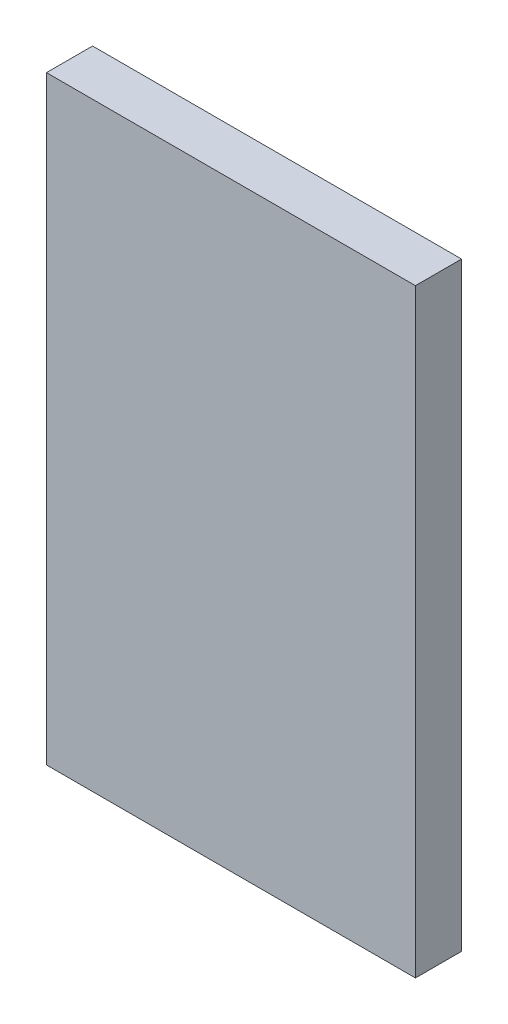
SolidWorks part; units mm, degrees
ref_plane "Front Plane" through (0, 0, 0) normal (0, 0, 1) x (1, 0, 0)
ref_plane "Top Plane" through (0, 0, 0) normal (0, 1, 0) x (1, 0, 0)
ref_plane "Right Plane" through (0, 0, 0) normal (1, 0, 0) x (0, 0, -1)
sketch "Sketch1" plane through (0, 0, 0) normal (0, 0, 1) x (1, 0, 0)
  line L1 (-10, 0) -> (10, 0)
  line L2 (-10, 0) -> (-10, 32.5)
  line L3 (-10, 32.5) -> (10, 32.5)
  line L4 (10, 0) -> (10, 32.5)
  point P4 (0, 0)
  dimension "D1" = 20
  dimension "D2" = 32.5
  dimension "D3" = 0
  dimension "D4" = 10
extrude "Boss-Extrude1" add sketch "Sketch1" along normal blind 2.5
sketch "Sketch2" plane through (0, 0, 0) normal (0, 0, -1) x (-1, 0, 0)
  line L0 (10, 0) -> (-10, 0) construction
  line L1 (-2.5, 0) -> (2.5, 0)
  line L2 (-2.5, 0) -> (-2.5, 7.5)
  line L3 (-2.5, 7.5) -> (2.5, 7.5)
  line L4 (2.5, 0) -> (2.5, 7.5)
  line L5 (10, 32.5) -> (10, 0) construction
  dimension "D1" = 0
  dimension "D2" = 5
  dimension "D3" = 7.5
  dimension "D4" = 7.5
extrude "Boss-Extrude2" add sketch "Sketch2" along normal blind 2
fillet "Fillet1" radius 1 8 edges at (0, 0, -2) (-2.5, 3.75, -2) (0, 7.5, -2) (2.5, 3.75, -2) (2.5, 0, -1) (-2.5, 0, -1) (-2.5, 7.5, -1) (2.5, 7.5, -1)
